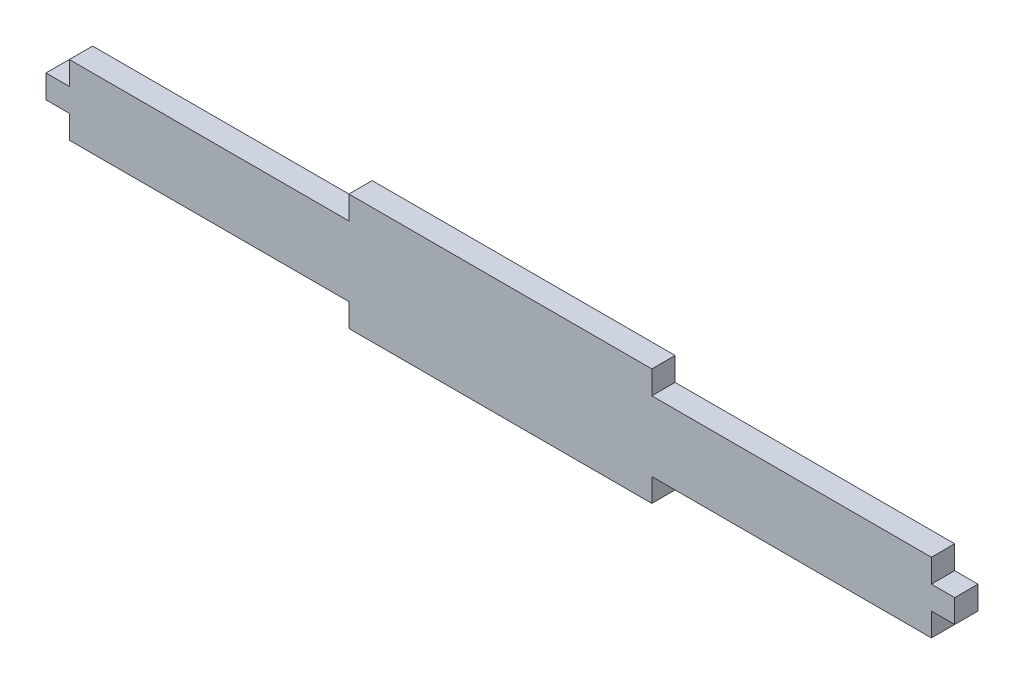
SolidWorks part; units mm, degrees
ref_plane "Front Plane" through (0, 0, 0) normal (0, 0, 1) x (1, 0, 0)
ref_plane "Top Plane" through (0, 0, 0) normal (0, 1, 0) x (1, 0, 0)
ref_plane "Right Plane" through (0, 0, 0) normal (1, 0, 0) x (0, 0, -1)
sketch "Sketch1" plane through (0, 0, 0) normal (0, 0, 1) x (1, 0, 0)
  line L1 (-58.5, -7.5) -> (58.5, -7.5) construction
  line L2 (-58.5, -7.5) -> (-58.5, 7.5) construction
  line L3 (-58.5, 7.5) -> (58.5, 7.5) construction
  line L4 (58.5, -7.5) -> (58.5, 7.5) construction
  line L5 (-58.5, -7.5) -> (58.5, 7.5) construction
  line L6 (-58.5, 7.5) -> (58.5, -7.5) construction
  line L11 (-46.4777, -5.9587) -> (46.4777, 5.9587) construction
  line L12 (-46.4777, 5.9587) -> (46.4777, -5.9587) construction
  line L14 (-19.5, -7.5) -> (19.5, -7.5)
  line L19 (58.5, -1.5) -> (58.5, 1.5)
  line L24 (19.5, 7.5) -> (-19.5, 7.5)
  line L29 (-58.5, 1.5) -> (-58.5, -1.5)
  line L32 (-19.5, -7.5) -> (-19.5, -4.5)
  line L33 (-19.5, -4.5) -> (-58.5, -4.5) construction
  line L34 (-19.5, 7.5) -> (-19.5, 4.5)
  line L35 (-19.5, 4.5) -> (-58.5, 4.5) construction
  line L38 (19.5, 7.5) -> (19.5, 4.5)
  line L39 (19.5, 4.5) -> (58.5, 4.5) construction
  line L42 (58.5, -4.5) -> (19.5, -4.5) construction
  line L43 (19.5, -4.5) -> (19.5, -7.5)
  line L44 (58.5, 1.5) -> (55.5, 1.5)
  line L45 (55.5, 1.5) -> (55.5, 4.5)
  line L46 (58.5, -1.5) -> (55.5, -1.5)
  line L47 (55.5, -1.5) -> (55.5, -4.5)
  line L48 (-58.5, 1.5) -> (-55.5, 1.5)
  line L49 (-55.5, 1.5) -> (-55.5, 4.5)
  line L50 (-58.5, -1.5) -> (-55.5, -1.5)
  line L51 (-55.5, -1.5) -> (-55.5, -4.5)
  line L52 (19.5, 4.5) -> (55.5, 4.5)
  line L53 (55.5, -4.5) -> (19.5, -4.5)
  line L54 (-55.5, 4.5) -> (-19.5, 4.5)
  line L55 (-19.5, -4.5) -> (-55.5, -4.5)
  point P0 (0, 0)
  point P6 (0, 0)
  dimension "D1" = 117
  dimension "D2" = 15
  dimension "D3" = 3
extrude "Boss-Extrude1" add sketch "Sketch1" along normal blind 3
